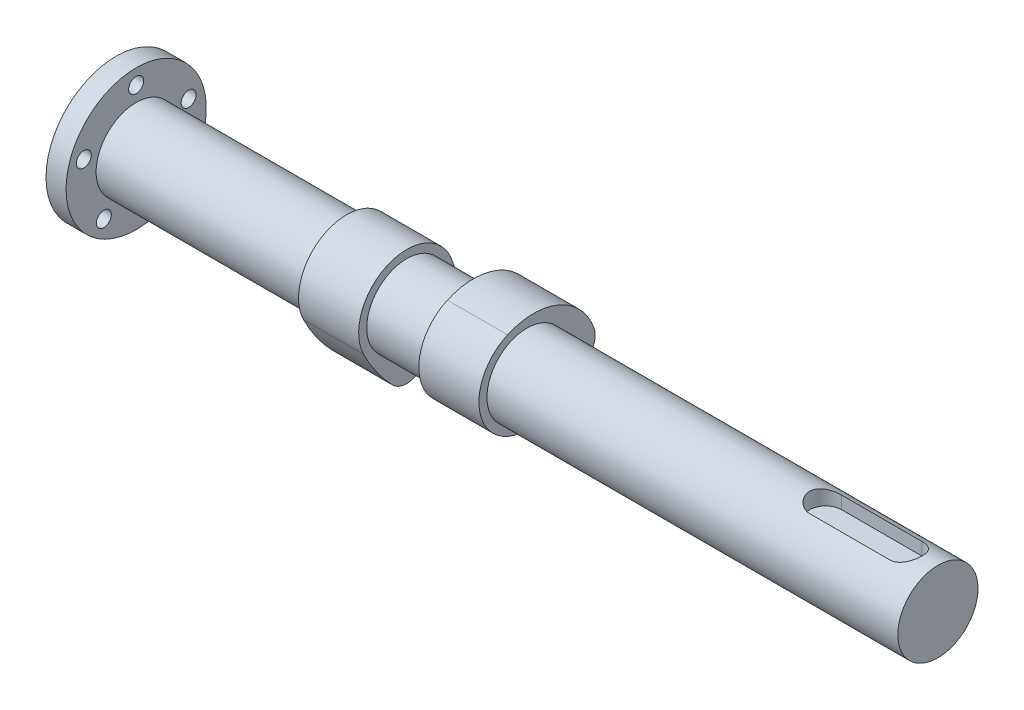
SolidWorks part; units mm, degrees
material "Brass"
ref_plane "Front Plane" through (0, 0, 0) normal (0, 0, 1) x (1, 0, 0)
ref_plane "Top Plane" through (0, 0, 0) normal (0, 1, 0) x (1, 0, 0)
ref_plane "Right Plane" through (0, 0, 0) normal (1, 0, 0) x (0, 0, -1)
sketch "Sketch1" plane through (0, 0, 0) normal (1, 0, 0) x (0, 0, -1)
  circle A0 centre (0, 0) radius 40
  dimension "D1" = 80
extrude "Boss-Extrude1" add sketch "Sketch1" against normal blind 300 and the other way blind 500
sketch "Sketch2" plane through (0, 0, 0) normal (1, 0, 0) x (0, 0, -1)
  line L0 (0, 0) -> (47.9878, 0) construction
  arc A0 (-19.4684, 43.8746) -> (21.2249, -43.0523) centre (0, 0) ccw
  arc A1 (61.9182, -14.3508) -> (66.8507, 6.6477) centre (47.9878, 0) ccw
  arc A2 (-19.4684, 43.8746) -> (66.8507, 6.6477) centre (6.4895, -14.6249) cw
  arc A3 (61.9182, -14.3508) -> (21.2249, -43.0523) centre (-49.5248, 100.4554) cw
  dimension "D1" = 96
  dimension "D2" = 40
  dimension "D3" = 64
  dimension "D4" = 160
  dimension "D5" = 50
extrude "Boss-Extrude2" add sketch "Sketch2" along normal mid plane 60 from offset 60 separate body
mirror "Mirror3" about plane through (0, 0, 0) normal (1, 0, 0) of bodies 102
move or copy body "Body-Move/Copy1" bodies to move or copy 105 copy no rotation origin (0, 0, 0) rotation axis (-1, 0, 0) rotation angle 90
ref_plane "Plane1" through (0, 40, 0) normal (0, 1, 0) x (1, 0, 0)
sketch "Sketch4" plane through (0, 40, 0) normal (0, 1, 0) x (1, 0, 0)
  line L0 (500, 0) -> (73.4899, 0) construction
  line L1 (500, -40) -> (500, 40) construction
  line L2 (388, 0) -> (468, 0) construction
  line L3 (388, 16) -> (468, 16)
  line L4 (388, -16) -> (468, -16)
  arc A0 (388, 16) -> (388, -16) centre (388, 0) ccw
  arc A1 (468, -16) -> (468, 16) centre (468, 0) ccw
  point P7 (428, 0)
  dimension "D3" = 16
  dimension "D1" = 80
  dimension "D2" = 32
extrude "Cut-Extrude1" cut sketch "Sketch4" against normal blind 16
sketch "Sketch5" plane through (-300, 0, 0) normal (-1, 0, 0) x (0, 0, 1)
  circle A0 centre (0, 0) radius 70
  dimension "D1" = 140
extrude "Boss-Extrude3" add sketch "Sketch5" along normal blind 20
sketch "Sketch6" plane through (-320, 0, 0) normal (-1, 0, 0) x (0, 0, 1)
  circle A0 centre (0, 0) radius 55 construction
  circle A1 centre (0, 55) radius 7.5
  dimension "D1" = 110
  dimension "D2" = 15
extrude "Cut-Extrude2" cut sketch "Sketch6" against normal blind 20
pattern_circular "CirPattern1" count 5 over 360 about axis through (0, 0, 0) along (1, 0, 0) of "Cut-Extrude2"
